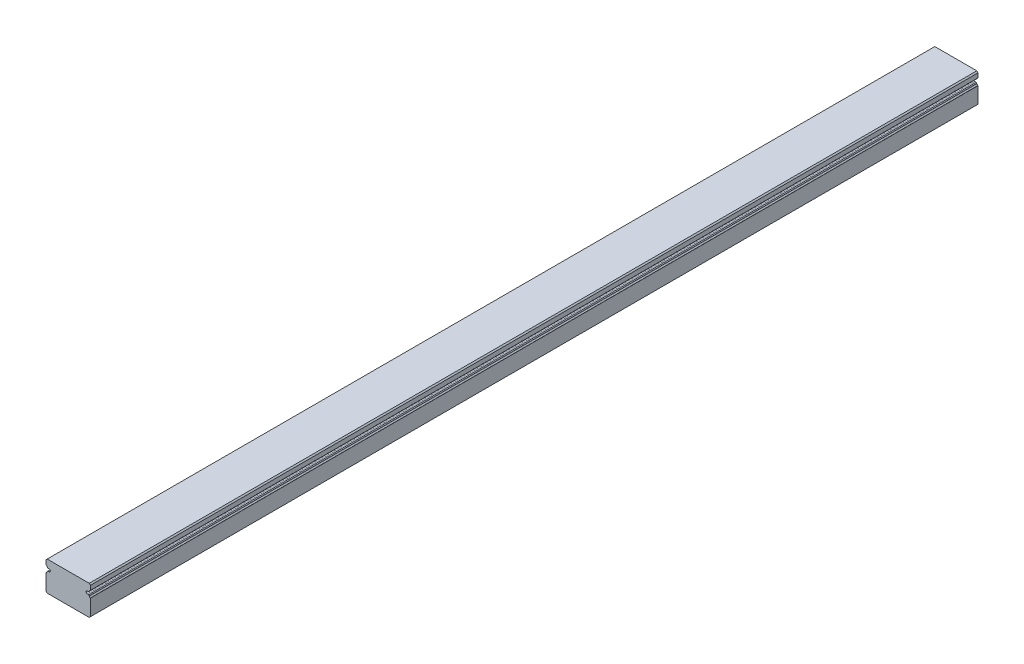
SolidWorks part; units mm, degrees
material "Простая углеродистая сталь"
ref_plane "Спереди" through (0, 0, 0) normal (0, 0, 1) x (1, 0, 0)
ref_plane "Сверху" through (0, 0, 0) normal (0, 1, 0) x (1, 0, 0)
ref_plane "Справа" through (0, 0, 0) normal (1, 0, 0) x (0, 0, -1)
sketch "Model" plane through (0, 0, 0) normal (0, 0, 1) x (1, 0, 0)
  line L0 (-7.1, -5) -> (7.1, -5)
  line L1 (7.1, -5) -> (7.5, -4.6)
  line L2 (7.5, -4.6) -> (7.5, 0.85)
  line L3 (7.5, 0.85) -> (7.4639, 0.8921)
  line L4 (7.1196, 1.2938) -> (6.9, 1.55)
  line L5 (6.9, 1.55) -> (6.5, 1.55)
  line L6 (6.5, 2.45) -> (6.9, 2.45)
  line L7 (6.9, 2.45) -> (7.1196, 2.7062)
  line L8 (7.4639, 3.1079) -> (7.5, 3.15)
  line L9 (7.5, 3.15) -> (7.5, 4.6)
  line L10 (7.5, 4.6) -> (7.1, 5)
  line L11 (7.1, 5) -> (-7.1, 5)
  line L12 (-7.1, 5) -> (-7.5, 4.6)
  line L13 (-7.5, 4.6) -> (-7.5, 3.15)
  line L14 (-7.5, 3.15) -> (-7.4639, 3.1079)
  line L15 (-7.1196, 2.7062) -> (-6.9, 2.45)
  line L16 (-6.9, 2.45) -> (-6.5, 2.45)
  line L17 (-6.5, 1.55) -> (-6.9, 1.55)
  line L18 (-6.9, 1.55) -> (-7.1196, 1.2938)
  line L19 (-7.4639, 0.8921) -> (-7.5, 0.85)
  line L20 (-7.5, 0.85) -> (-7.5, -4.6)
  line L21 (-7.5, -4.6) -> (-7.1, -5)
  arc A1 (7.1196, 1.2938) -> (7.4639, 0.8921) centre (7.5195, 1.2882) ccw
  arc A2 (6.5, 2.45) -> (6.5, 1.55) centre (6.5, 2) ccw
  arc A3 (7.4639, 3.1079) -> (7.1196, 2.7062) centre (7.5195, 2.7118) ccw
  arc A4 (-7.1196, 2.7062) -> (-7.4639, 3.1079) centre (-7.5195, 2.7118) ccw
  arc A5 (-6.5, 1.55) -> (-6.5, 2.45) centre (-6.5, 2) ccw
  arc A6 (-7.4639, 0.8921) -> (-7.1196, 1.2938) centre (-7.5195, 1.2882) ccw
extrude "База" add sketch "Model" along normal mid plane 300
